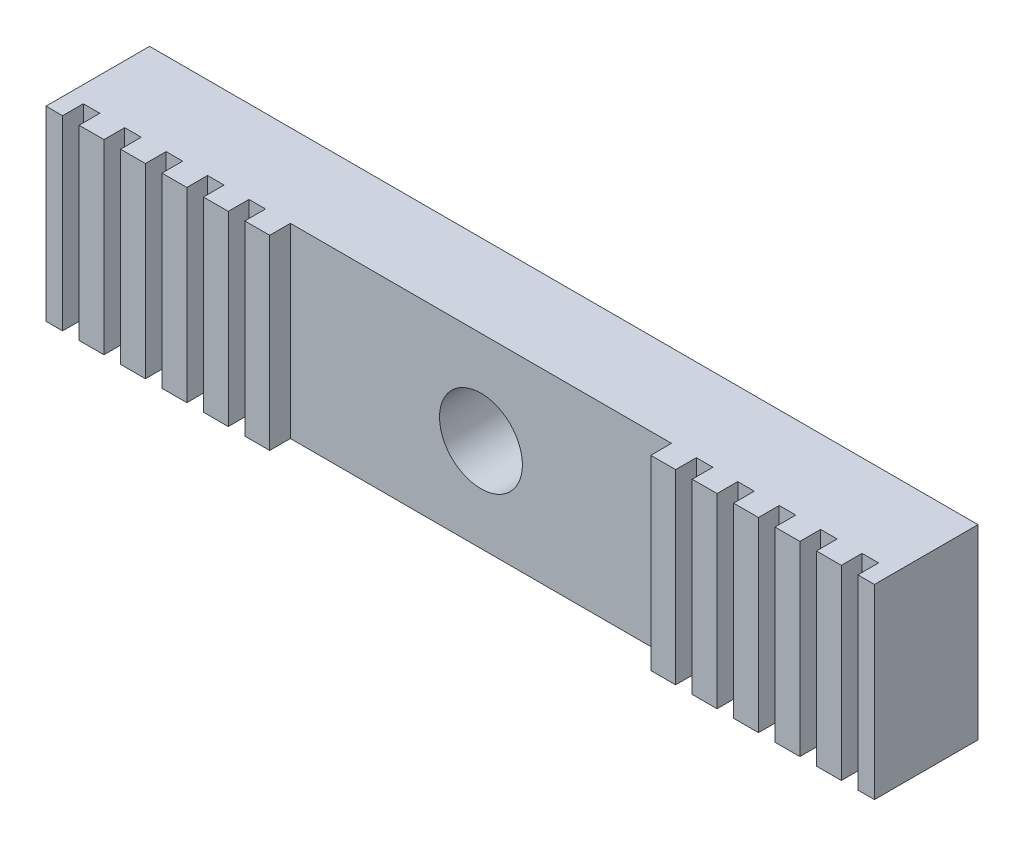
SolidWorks part; units mm, degrees
ref_plane "前基準面" through (0, 0, 0) normal (0, 0, 1) x (1, 0, 0)
ref_plane "上基準面" through (0, 0, 0) normal (0, 1, 0) x (1, 0, 0)
ref_plane "右基準面" through (0, 0, 0) normal (1, 0, 0) x (0, 0, -1)
sketch "草圖1" plane through (0, 0, 0) normal (0, 0, 1) x (1, 0, 0)
  line L1 (-20, 4.5) -> (20, 4.5)
  line L2 (-20, 4.5) -> (-20, -4.5)
  line L3 (-20, -4.5) -> (20, -4.5)
  line L4 (20, 4.5) -> (20, -4.5)
  circle A0 centre (0, 0) radius 2
  point P4 (0, 4.5)
  point P6 (-20, 0)
  dimension "D3" = 4
  dimension "D1" = 40
  dimension "D2" = 9
extrude "填料-伸長1" add sketch "草圖1" along normal blind 5
sketch "草圖2" plane through (0, -4.5, 0) normal (0, -1, 0) x (1, 0, 0)
  line L0 (-19.2, 5) -> (-19.2, 4)
  line L1 (-20, 5) -> (20, 5) construction
  line L2 (-19.2, 4) -> (-18.4, 4)
  line L3 (-18.4, 4) -> (-18.4, 5)
  line L4 (-18.4, 5) -> (-19.2, 5)
  line L5 (-20, 5) -> (-20, 0) construction
  line L6 (-17.2, 4) -> (-16.4, 4)
  line L7 (-17.2, 5) -> (-17.2, 4)
  line L8 (-16.4, 4) -> (-16.4, 5)
  line L9 (-16.4, 5) -> (-17.2, 5)
  line L10 (-15.2, 4) -> (-14.4, 4)
  line L11 (-15.2, 5) -> (-15.2, 4)
  line L12 (-14.4, 4) -> (-14.4, 5)
  line L13 (-14.4, 5) -> (-15.2, 5)
  line L14 (-13.2, 4) -> (-12.4, 4)
  line L15 (-13.2, 5) -> (-13.2, 4)
  line L16 (-12.4, 4) -> (-12.4, 5)
  line L17 (-12.4, 5) -> (-13.2, 5)
  line L18 (-11.2, 4) -> (-10.4, 4)
  line L19 (-11.2, 5) -> (-11.2, 4)
  line L20 (-10.4, 4) -> (-10.4, 5)
  line L21 (-10.4, 5) -> (-11.2, 5)
  line L22 (-9.2, 4) -> (-8.4, 4)
  line L23 (-9.2, 5) -> (-9.2, 4)
  line L25 (-8.4, 5) -> (-9.2, 5)
  line L26 (0, 0) -> (0, 5) construction
  line L27 (8.4, 5) -> (9.2, 5)
  line L29 (9.2, 5) -> (9.2, 4)
  line L30 (9.2, 4) -> (8.4, 4)
  line L31 (10.4, 5) -> (11.2, 5)
  line L32 (10.4, 4) -> (10.4, 5)
  line L33 (11.2, 5) -> (11.2, 4)
  line L34 (11.2, 4) -> (10.4, 4)
  line L35 (12.4, 5) -> (13.2, 5)
  line L36 (12.4, 4) -> (12.4, 5)
  line L37 (13.2, 5) -> (13.2, 4)
  line L38 (13.2, 4) -> (12.4, 4)
  line L39 (14.4, 5) -> (15.2, 5)
  line L40 (14.4, 4) -> (14.4, 5)
  line L41 (15.2, 5) -> (15.2, 4)
  line L42 (15.2, 4) -> (14.4, 4)
  line L43 (16.4, 5) -> (17.2, 5)
  line L44 (16.4, 4) -> (16.4, 5)
  line L45 (17.2, 5) -> (17.2, 4)
  line L46 (17.2, 4) -> (16.4, 4)
  line L47 (18.4, 5) -> (19.2, 5)
  line L48 (18.4, 4) -> (18.4, 5)
  line L49 (19.2, 4) -> (18.4, 4)
  line L50 (19.2, 5) -> (19.2, 4)
  line L51 (-8.4, 4) -> (8.4, 4)
  line L52 (8.4, 5) -> (-8.4, 5)
  line L54 (-8.4, 4) -> (-8.4, 5) [skipped]
  dimension "D1" = 1
  dimension "D2" = 0.8
  dimension "D3" = 0.8
  dimension "D5" = 1.2
  dimension "D4" = 6
extrude "除料-伸長1" cut sketch "草圖2" against normal through all
